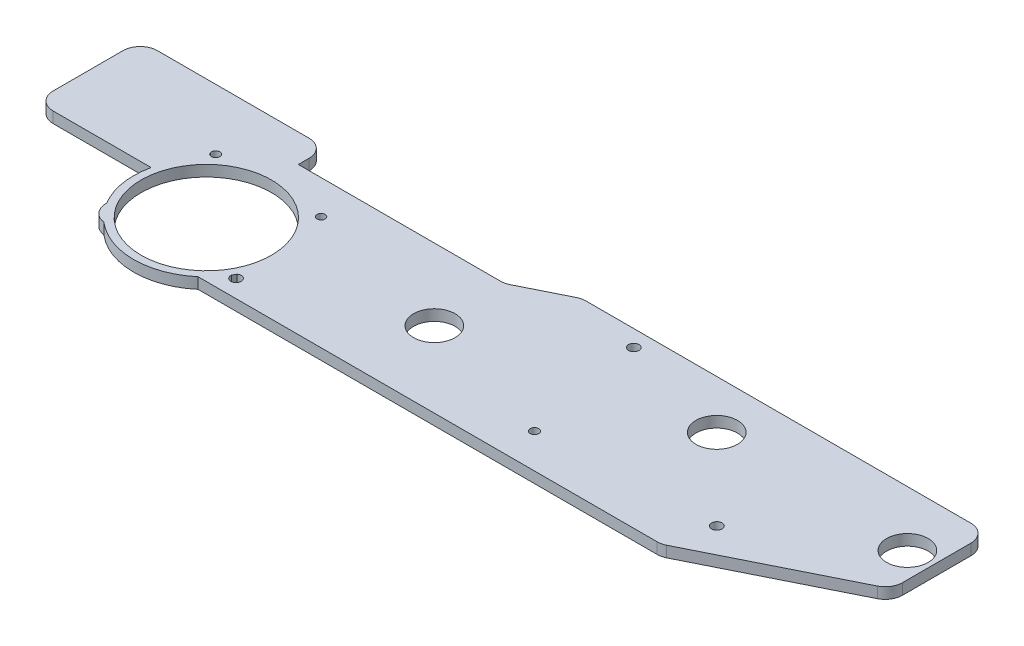
SolidWorks part; units mm, degrees
ref_plane "Front" through (0, 0, 0) normal (0, 0, 1) x (1, 0, 0)
ref_plane "Top" through (0, 0, 0) normal (0, 1, 0) x (1, 0, 0)
ref_plane "Right" through (0, 0, 0) normal (1, 0, 0) x (0, 0, -1)
sketch "Sketch1" plane through (0, 0, 0) normal (0, 1, 0) x (1, 0, 0)
  line L1 (0, 0) -> (210, 0)
  line L2 (0, 0) -> (0, -50)
  line L3 (0, -50) -> (210, -50)
  line L4 (210, 0) -> (210, -50)
  circle A7 centre (3.4895, -16.7877) radius 1.2117
  circle A8 centre (34.3726, -17.194) radius 1.1656
  circle A9 centre (37.5207, -44.9212) radius 1.5
  circle A10 centre (118.879, -40.0177) radius 1.25
  circle A11 centre (112.3021, -4.7393) radius 1.5
  circle A12 centre (168.9752, -37.4032) radius 1.5173
  dimension "D1" = 210
  dimension "D2" = 50
extrude "Boss-Extrude1" add sketch "Sketch1" along normal blind 3.175
sketch "Sketch2" plane through (0, 3.175, 0) normal (0, 1, 0) x (1, 0, 0)
  line L0 (210, 0) -> (0, 0) construction
  line L1 (0, 0) -> (0, -50) construction
  circle A0 centre (10, -26) radius 2
  circle A1 centre (10, -42) radius 2
  circle A2 centre (26, -26) radius 2
  circle A3 centre (26, -42) radius 2
  dimension "D1" = 16
  dimension "D2" = 16
  dimension "D3" = 16
  dimension "D4" = 26
  dimension "D5" = 10
  dimension "D6" = 10
  dimension "D7" = 26
  dimension "D8" = 16
extrude "Cut-Extrude1" cut sketch "Sketch2" against normal blind 10
sketch "Sketch3" plane through (0, 3.175, 0) normal (0, 1, 0) x (1, 0, 0)
  line L0 (210, 0) -> (0, 0) construction
  line L1 (210, 0) -> (0, 0) construction
  circle A0 centre (78.0103, -28.1) radius 6
  circle A1 centre (145.5313, -14) radius 6
  circle A2 centre (18, -34) radius 0.587
  circle A3 centre (26, -26) radius 2 construction
  circle A4 centre (202.6463, -16) radius 6
  dimension "D1" = 28.1
  dimension "D3" = 16
  dimension "D4" = 14
  dimension "D7" = 125.222
  dimension "D2" = 60.2996
  dimension "D5" = 8
  dimension "D6" = 8
  dimension "D8" = 57.15
extrude "Cut-Extrude2" cut sketch "Sketch3" against normal blind 57.15
sketch "Sketch4" [suppressed] plane through (0, 3.175, 0) normal (0, 1, 0) x (1, 0, 0)
  line L0 (3.4895, -16.7877) -> (18, -34)
  line L1 (3.4895, -20.6627) -> (5.9498, -23.5811)
  line L2 (18, -34) -> (34.3726, -17.194)
  line L3 (34.3726, -17.194) -> (75.8499, -28.1)
  line L4 (75.8499, -28.1) -> (37.5207, -44.9212)
  line L5 (7.3432, -17.194) -> (9.8664, -20.303)
  circle A0 centre (18, -34) radius 15.9299
  circle A1 centre (3.4895, -16.7877) radius 3.8751
  circle A2 centre (34.3726, -17.194) radius 3.7227
  circle A3 centre (37.5207, -44.9212) radius 3.8676
  circle A4 centre (75.8499, -28.1) radius 12.797
  circle A5 centre (112.3021, -4.7393) radius 5.1588
  circle A6 centre (118.879, -40.0177) radius 4.9035
  circle A7 centre (140.772, -16) radius 12.6375
  circle A8 centre (168.9752, -37.4032) radius 4.2066
  circle A9 centre (197.922, -16) radius 12.8
sketch "Sketch5" [suppressed] plane through (0, 3.175, 0) normal (0, 1, 0) x (1, 0, 0)
  line L0 (210, 0) -> (0, 0) construction
  line L2 (-0.6266, -16.7877) -> (37.5207, -16.7877)
  line L3 (-0.6266, -16.7877) -> (-0.6266, -44.9212)
  line L4 (-0.6266, -44.9212) -> (37.5207, -44.9212)
  line L5 (37.5207, -16.7877) -> (37.5207, -44.9212)
  line L6 (75.8499, -15.182) -> (37.5207, -15.182)
  line L7 (75.8499, -15.182) -> (75.8499, -44.9212)
  line L8 (75.8499, -44.9212) -> (37.5207, -44.9212)
  line L9 (37.5207, -15.182) -> (37.5207, -44.9212)
  line L10 (112.3021, -4.7393) -> (75.8499, -4.7393)
  line L11 (112.3021, -4.7393) -> (112.3021, -44.9212)
  line L12 (112.3021, -44.9212) -> (75.8499, -44.9212)
  line L13 (75.8499, -4.7393) -> (75.8499, -44.9212)
  line L14 (112.3021, -4.7393) -> (102.3945, -4.7393)
  line L16 (112.3021, -4.7393) -> (112.3021, 0)
  line L17 (112.3021, 0) -> (102.3945, 0)
  line L18 (102.3945, -4.7393) -> (102.3945, 0)
  line L19 (210, -50) -> (210, 0) construction
  line L20 (112.3021, -4.7393) -> (123.1553, -4.7393)
  line L21 (112.3021, -4.7393) -> (112.3021, 0)
  line L22 (112.3021, 0) -> (123.1553, 0)
  line L23 (123.1553, -4.7393) -> (123.1553, 0)
  line L24 (112.3021, -4.7393) -> (140.772, -4.7393)
  line L25 (112.3021, -4.7393) -> (112.3021, -40.0177)
  line L26 (112.3021, -40.0177) -> (140.772, -40.0177)
  line L27 (140.772, -4.7393) -> (140.772, -40.0177)
  line L28 (140.772, -16) -> (168.9752, -16)
  line L29 (140.772, -16) -> (140.772, -40.0177)
  line L30 (140.772, -40.0177) -> (168.9752, -40.0177)
  line L31 (168.9752, -16) -> (168.9752, -40.0177)
  line L32 (168.9752, -4.7393) -> (210, -4.7393)
  line L33 (168.9752, -4.7393) -> (168.9752, -40.0177)
  line L34 (168.9752, -40.0177) -> (210, -40.0177)
  line L35 (210, -4.7393) -> (210, -40.0177)
  line L36 (0, -50) -> (210, -50) construction
  line L37 (160.7629, -40.0177) -> (177.2091, -40.0177)
  line L38 (160.7629, -40.0177) -> (160.7629, -44.9212)
  line L39 (160.7629, -44.9212) -> (177.2091, -44.9212)
  line L40 (177.2091, -40.0177) -> (177.2091, -44.9212)
  line L41 (112.3021, -40.0177) -> (126.3591, -40.0177)
  line L42 (112.3021, -40.0177) -> (112.3021, -47.7828)
  line L43 (112.3021, -47.7828) -> (126.3591, -47.7828)
  line L44 (126.3591, -40.0177) -> (126.3591, -47.7828)
  line L45 (30.5963, -44.9212) -> (44.6115, -44.9212)
  line L46 (30.5963, -44.9212) -> (30.5963, -50)
  line L47 (30.5963, -50) -> (44.6115, -50)
  line L48 (44.6115, -44.9212) -> (44.6115, -50)
  line L50 (-0.6266, -44.9212) -> (30.5963, -44.9212)
  line L51 (-0.6266, -44.9212) -> (-0.6266, -50)
  line L52 (-0.6266, -50) -> (30.5963, -50)
  line L53 (30.5963, -44.9212) -> (30.5963, -50)
  circle A0 centre (3.4895, -16.7877) radius 4.1161
  circle A1 centre (34.3726, -17.194) radius 3.8132
  circle A2 centre (75.8499, -28.1) radius 12.918
  circle A3 centre (112.3021, -4.7393) radius 5.2663
  circle A4 centre (140.772, -16) radius 13.0245
  circle A5 centre (197.922, -16) radius 12.3805
  circle A6 centre (168.9752, -37.4032) radius 4.7643
  circle A7 centre (118.879, -40.0177) radius 5.279
  circle A8 centre (37.5207, -44.9212) radius 4.2049
  line M12 (0, 0) -> (0, -50)
  line M13 (0, -50) -> (210, -50)
  line M14 (210, -50) -> (210, 0)
  line M15 (210, 0) -> (0, 0)
extrude "Cut-Extrude5" [suppressed] cut sketch "Sketch5" against normal blind 11.52 contours A5 L32 L23 L24 A4 L28 L33 M14 M15 | A1 L6 L13 L10 L18 A0 L2 M15 M12 | L8 L48 L34 L40 L39 L38 L30 L26 L44 L43 L42 L12 M13 M14
fillet "Fillet1" [suppressed] radius 5
sketch "Sketch10" plane through (0, 3.175, 0) normal (0, 1, 0) x (1, 0, 0)
  line L0 (210, -27.8594) -> (165.5029, -50)
  line L1 (210, -50) -> (210, 0) construction
  line L2 (0, -50) -> (210, -50) construction
  line L3 (165.5029, -50) -> (210, -50)
  line L4 (210, -50) -> (210, -27.8594)
  line L5 (92.5326, 0) -> (77.6548, -7.4028)
  line L6 (210, 0) -> (0, 0) construction
  line L7 (77.6548, -7.4028) -> (0, -7.4028)
  line L8 (0, 0) -> (0, -50) construction
  line L9 (0, -7.4028) -> (0, 0)
  line L10 (0, 0) -> (92.5326, 0)
extrude "Cut-Extrude7" cut sketch "Sketch10" against normal blind 10
fillet "Fillet3" radius 5 7 edges at (0, 1.5875, 50) (0, 1.5875, 7.4028) (77.6548, 1.5875, 7.4028) (92.5326, 1.5875, 0) (210, 1.5875, 0) (210, 1.5875, 27.8594) (165.5029, 1.5875, 50)
sketch "Sketch11" plane through (0, 3.175, 0) normal (0, 1, 0) x (1, 0, 0)
  circle A0 centre (18, -34) radius 18.5
  circle A1 centre (10, -26) radius 2
  circle A2 centre (10, -42) radius 2
  circle A3 centre (26, -26) radius 2
  circle A4 centre (26, -42) radius 2
extrude "Boss-Extrude4" add sketch "Sketch11" against normal blind 3.175
sketch "Sketch12" plane through (0, 3.175, 0) normal (0, 1, 0) x (1, 0, 0)
  circle A0 centre (18, -34) radius 21
  circle A1 centre (10, -26) radius 2 construction
  circle A2 centre (10, -42) radius 2 construction
  dimension "D1" = 8
  dimension "D2" = 8
extrude "Boss-Extrude5" add sketch "Sketch12" against normal blind 3.175
sketch "Sketch13" plane through (0, 3.175, 0) normal (0, 1, 0) x (1, 0, 0)
  circle A0 centre (18, -34) radius 18.85
extrude "Cut-Extrude8" cut sketch "Sketch13" against normal blind 3.175
sketch "Sketch14" plane through (0, 3.175, 0) normal (0, 1, 0) x (1, 0, 0)
  line L0 (0, -12.4028) -> (0, -23.1833) construction
  line L1 (0, -29.4491) -> (-35.83, -29.4491)
  line L2 (0, -29.4491) -> (0, 0.7272)
  line L3 (0, 0.7272) -> (-35.83, 0.7272)
  line L4 (-35.83, -29.4491) -> (-35.83, 0.7272)
  line L5 (5, -7.4028) -> (76.4796, -7.4028) construction
  line L8 (0, 0.7272) -> (18, 0.7272)
  line L9 (0, 0.7272) -> (0, -12.2485)
  line L10 (0, -12.2485) -> (18, -12.2485)
  line L11 (18, 0.7272) -> (18, -12.2485)
  line M20 (76.4796, -7.4028) -> (5, -7.4028)
  arc M21 (5, -7.4028) -> (0, -12.4028) centre (5, -12.4028) ccw
  line M22 (0, -12.4028) -> (0, -23.1833)
  arc M23 (0, -23.1833) -> (0, -44.8167) centre (18, -34) ccw
  dimension "D4" = 18
  dimension "D1" = 8.13
  dimension "D2" = 35.83
  dimension "D3" = 30.1763
extrude "Boss-Extrude6" add sketch "Sketch14" against normal blind 3.175 contours L4 L1 L2 L3 M23 M22 | L11 L8 L2 L10 M21 M20
fillet "Fillet4" radius 5 3 edges at (18, 1.5875, -0.7272) (-35.83, 1.5875, 29.4491) (-35.83, 1.5875, -0.7272)
